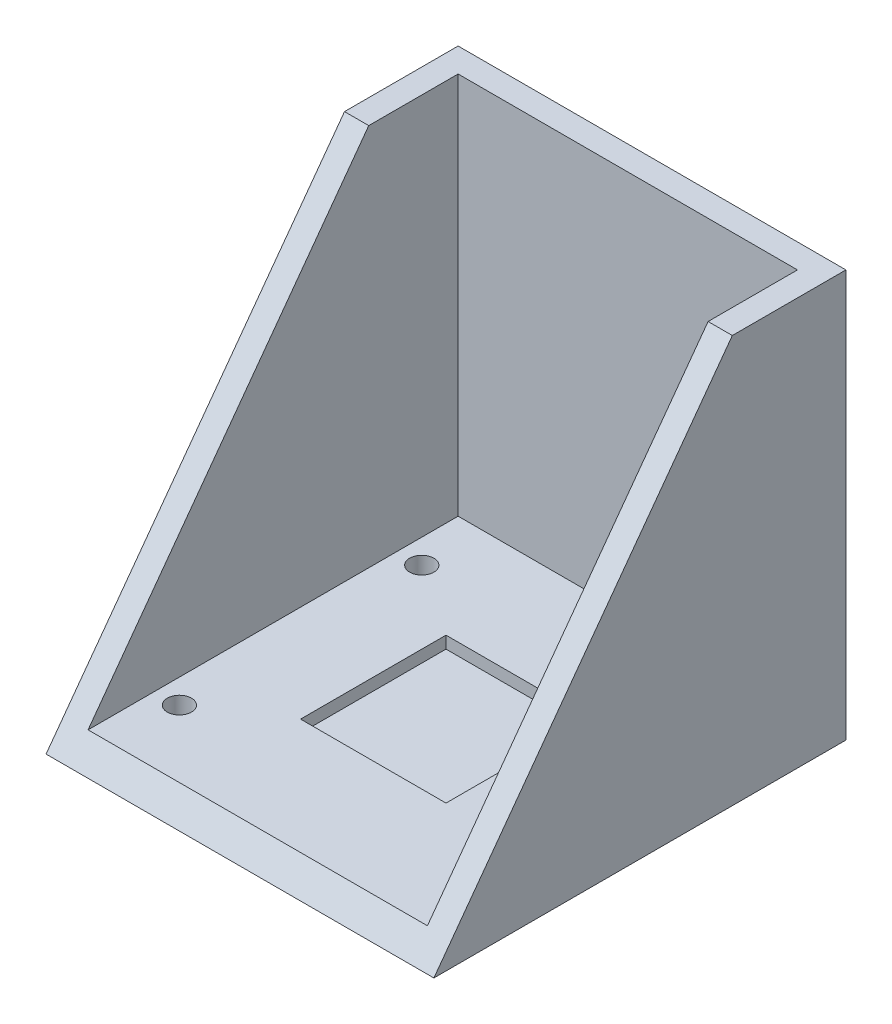
SolidWorks part; units mm, degrees
material "1060 Alloy"
ref_plane "Front Plane" through (0, 0, 0) normal (0, 0, 1) x (1, 0, 0)
ref_plane "Top Plane" through (0, 0, 0) normal (0, 1, 0) x (1, 0, 0)
ref_plane "Right Plane" through (0, 0, 0) normal (1, 0, 0) x (0, 0, -1)
sketch "Sketch1" plane through (0, 0, 0) normal (0, 1, 0) x (1, 0, 0)
  line L1 (-101.6, -107.95) -> (101.6, -107.95)
  line L2 (-101.6, -107.95) -> (-101.6, 107.95)
  line L3 (-101.6, 107.95) -> (101.6, 107.95)
  line L4 (101.6, -107.95) -> (101.6, 107.95)
  line L5 (-101.6, -107.95) -> (101.6, 107.95) construction
  line L6 (-101.6, 107.95) -> (101.6, -107.95) construction
  point P0 (0, 0)
  dimension "D1" = 203.2
  dimension "D2" = 215.9
extrude "Boss-Extrude1" add sketch "Sketch1" along normal blind 213.36
shell "Shell2" thickness 12.7
sketch "Sketch2" plane through (0, 12.7, 0) normal (0, 1, 0) x (1, 0, 0)
  line L1 (-38.1, -38.1) -> (38.1, -38.1)
  line L2 (-38.1, -38.1) -> (-38.1, 38.1)
  line L3 (-38.1, 38.1) -> (38.1, 38.1)
  line L4 (38.1, -38.1) -> (38.1, 38.1)
  line L5 (-38.1, -38.1) -> (38.1, 38.1) construction
  line L6 (-38.1, 38.1) -> (38.1, -38.1) construction
  point P0 (0, 0)
  dimension "D1" = 76.2
  dimension "D2" = 76.2
extrude "Cut-Extrude1" cut sketch "Sketch2" against normal blind 6.35
sketch "Sketch3" plane through (0, 12.7, 0) normal (0, 1, 0) x (1, 0, 0)
  line L1 (-76.2, -63.5) -> (76.2, -63.5) construction
  line L2 (-76.2, -63.5) -> (-76.2, 63.5) construction
  line L3 (-76.2, 63.5) -> (76.2, 63.5) construction
  line L4 (76.2, -63.5) -> (76.2, 63.5) construction
  line L5 (-76.2, -63.5) -> (76.2, 63.5) construction
  line L6 (-76.2, 63.5) -> (76.2, -63.5) construction
  circle A0 centre (-76.2, 63.5) radius 6.35
  circle A1 centre (-76.2, -63.5) radius 6.35
  circle A2 centre (76.2, 63.5) radius 6.35
  circle A3 centre (76.2, -63.5) radius 6.35
  point P0 (0, 0)
  dimension "D3" = 12.7
  dimension "D4" = 12.7
  dimension "D5" = 12.7
  dimension "D6" = 12.7
  dimension "D1" = 152.4
  dimension "D2" = 127
extrude "Cut-Extrude2" cut sketch "Sketch3" against normal through all
sketch "Sketch4" plane through (101.6, 0, 0) normal (1, 0, 0) x (0, 0, -1)
  line L0 (48.4218, 213.36) -> (-107.95, 0)
  line L1 (-107.95, 213.36) -> (107.95, 213.36) construction
  line L2 (-107.95, 0) -> (-107.95, 213.36)
  line L3 (-107.95, 213.36) -> (48.4218, 213.36)
extrude "Cut-Extrude3" cut sketch "Sketch4" against normal through all
sketch "Sketch5" plane through (0, 0, 0) normal (0, -1, 0) x (1, 0, 0)
  line L1 (-76.2, -63.5) -> (76.2, -63.5) construction
  line L2 (-76.2, -63.5) -> (-76.2, 63.5) construction
  line L3 (-76.2, 63.5) -> (76.2, 63.5) construction
  line L4 (76.2, -63.5) -> (76.2, 63.5) construction
  line L5 (-76.2, -63.5) -> (76.2, 63.5) construction
  line L6 (-76.2, 63.5) -> (76.2, -63.5) construction
  point P0 (0, 0)
  dimension "D1" = 152.4
  dimension "D2" = 127
